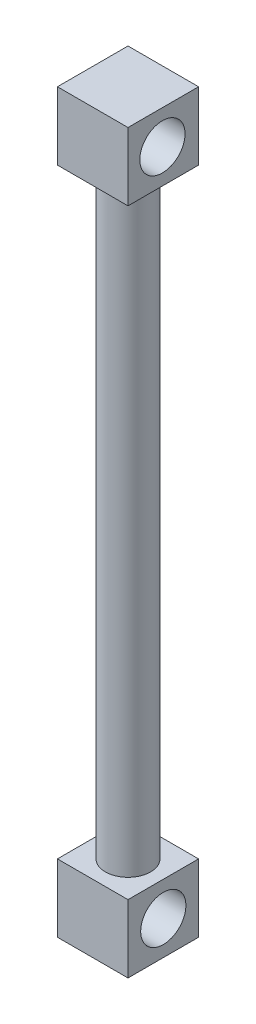
SolidWorks part; units mm, degrees
ref_plane "Front Plane" through (0, 0, 0) normal (0, 0, 1) x (1, 0, 0)
ref_plane "Top Plane" through (0, 0, 0) normal (0, 1, 0) x (1, 0, 0)
ref_plane "Right Plane" through (0, 0, 0) normal (1, 0, 0) x (0, 0, -1)
sketch "Sketch2" plane through (0, 0, 0) normal (0, 0, 1) x (1, 0, 0)
  line L0 (0, 0.75) -> (0.78, 0.75)
  line L1 (0, 0) -> (1.56, 0)
  line L2 (0, 0) -> (0, 1.5)
  line L3 (0, 1.5) -> (1.56, 1.5)
  line L4 (1.56, 0) -> (1.56, 1.5)
  line L5 (0.78, 0.75) -> (0.78, -14.78)
  line L7 (0, -14.78) -> (1.56, -14.78)
  line L8 (0, -14.78) -> (0, -13.28)
  line L9 (0, -13.28) -> (1.56, -13.28)
  line L10 (1.56, -14.78) -> (1.56, -13.28)
  dimension "D1" = 1.5
  dimension "D2" = 1.56
  dimension "D3" = 15.53
  dimension "D4" = 1.5
  dimension "D5" = 1.56
extrude "Boss-Extrude1" add sketch "Sketch2" along normal blind 1.56 contours L9 L8 L7 L5 | L7 L10 L9 L5 | L0 L5 L1 L4 L3 L2 | L5 L0 L2 L1
sketch "Sketch3" plane through (0, 0, 0) normal (0, -1, 0) x (1, 0, 0)
  line L0 (0, 0.78) -> (1.56, 0.78)
  line L1 (0, 1.56) -> (0, 0) construction
  line L2 (1.56, 1.56) -> (1.56, 0) construction
  circle A0 centre (0.78, 0.78) radius 0.5
extrude "Boss-Extrude2" add sketch "Sketch3" along normal blind 14 contours A0
sketch "Sketch4" plane through (0, 0, 0) normal (-1, 0, 0) x (0, 0, 1)
  line L0 (0, 0.75) -> (1.5988, 0.75)
  line L1 (0, 0) -> (0, 1.5) construction
  circle A0 centre (0.7994, 0.75) radius 0.5
extrude "Cut-Extrude1" cut sketch "Sketch4" against normal blind 14 contours A0
sketch "Sketch5" plane through (0, 0, 0) normal (-1, 0, 0) x (0, 0, 1)
  circle A0 centre (0.78, -14.03) radius 0.5
extrude "Cut-Extrude2" cut sketch "Sketch5" against normal blind 14
